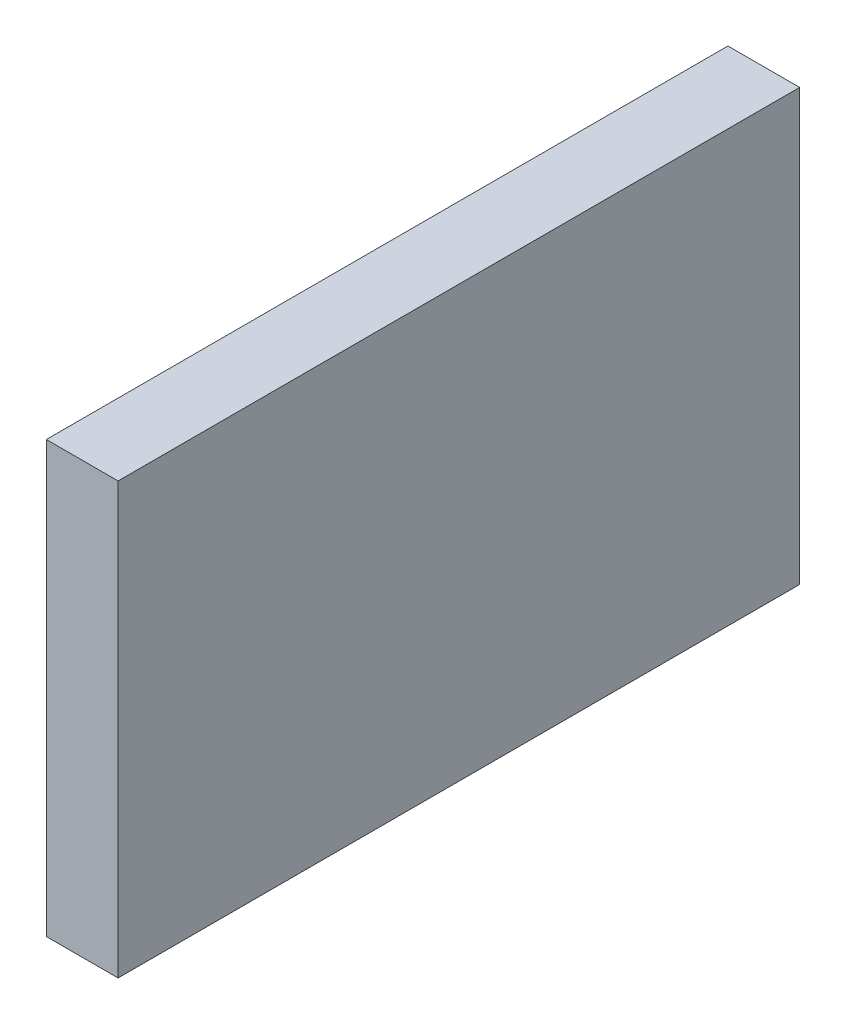
SolidWorks part; units mm, degrees
ref_plane "Front Plane" through (0, 0, 0) normal (0, 0, 1) x (1, 0, 0)
ref_plane "Top Plane" through (0, 0, 0) normal (0, 1, 0) x (1, 0, 0)
ref_plane "Right Plane" through (0, 0, 0) normal (1, 0, 0) x (0, 0, -1)
sketch "Sketch1" plane through (0, 0, 0) normal (0, 0, 1) x (1, 0, 0)
  line L1 (230, 40) -> (210, 40)
  line L2 (230, 40) -> (230, -80)
  line L3 (230, -80) -> (210, -80)
  line L4 (210, 40) -> (210, -80)
  dimension "D1" = 20
  dimension "D2" = 120
extrude "Boss-Extrude1" add sketch "Sketch1" along normal blind 190
